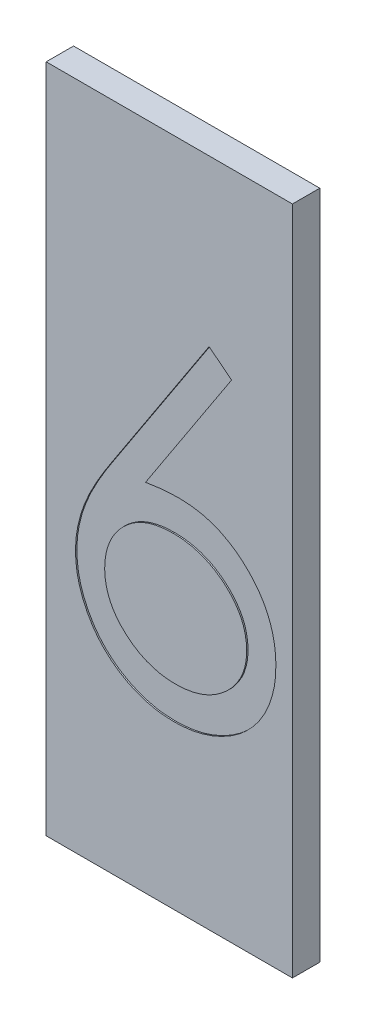
SolidWorks part; units mm, degrees
ref_plane "正面" through (0, 0, 0) normal (0, 0, 1) x (1, 0, 0)
ref_plane "平面" through (0, 0, 0) normal (0, 1, 0) x (1, 0, 0)
ref_plane "右側面" through (0, 0, 0) normal (1, 0, 0) x (0, 0, -1)
sketch "ｽｹｯﾁ1" plane through (0, 0, 0) normal (0, 0, 1) x (1, 0, 0)
  line L0 (18, 0) -> (0, 0)
  line L1 (18, 49) -> (0, 49)
  line L2 (0, 0) -> (0, 49)
  line L4 (18, 0) -> (18, 49)
extrude "ﾎﾞｽ - 押し出し1" add sketch "ｽｹｯﾁ1" along normal blind 2
sketch "ｽｹｯﾁ2" plane through (0, 0, 2) normal (0, 0, 1) x (1, 0, 0)
  text T0 "6" font "Century Gothic" height in points 90
extrude "ｶｯﾄ - 押し出し1" cut sketch "ｽｹｯﾁ2" against normal blind 0.1
